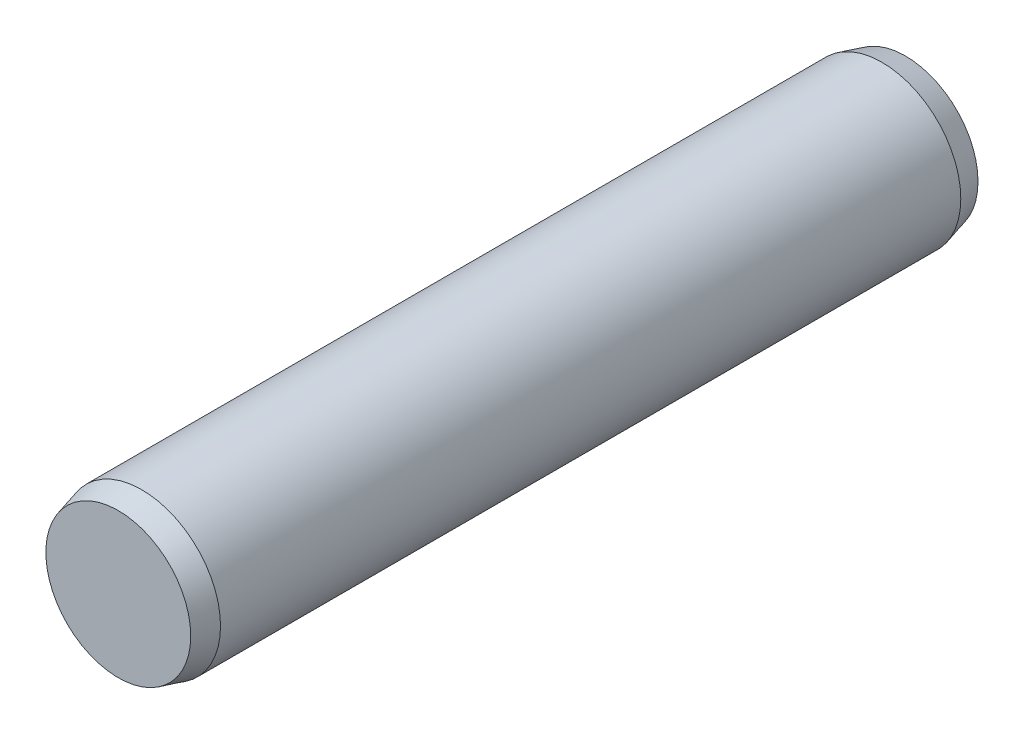
SolidWorks part; units mm, degrees
ref_plane "前视基准面" through (0, 0, 0) normal (0, 0, 1) x (1, 0, 0)
ref_plane "上视基准面" through (0, 0, 0) normal (0, 1, 0) x (1, 0, 0)
ref_plane "右视基准面" through (0, 0, 0) normal (1, 0, 0) x (0, 0, -1)
sketch "草图1" plane through (0, 0, 0) normal (0, 0, 1) x (1, 0, 0)
  circle A0 centre (0, 0) radius 2.5
  dimension "D1" = 5
extrude "凸台-拉伸1" add sketch "草图1" along normal mid plane 25
chamfer "倒角1" distance 0.2 angle 75 1 edges at (2.5, 0, 12.5)
chamfer "倒角2" distance 0.2 angle 75 1 edges at (2.5, 0, -12.5)
